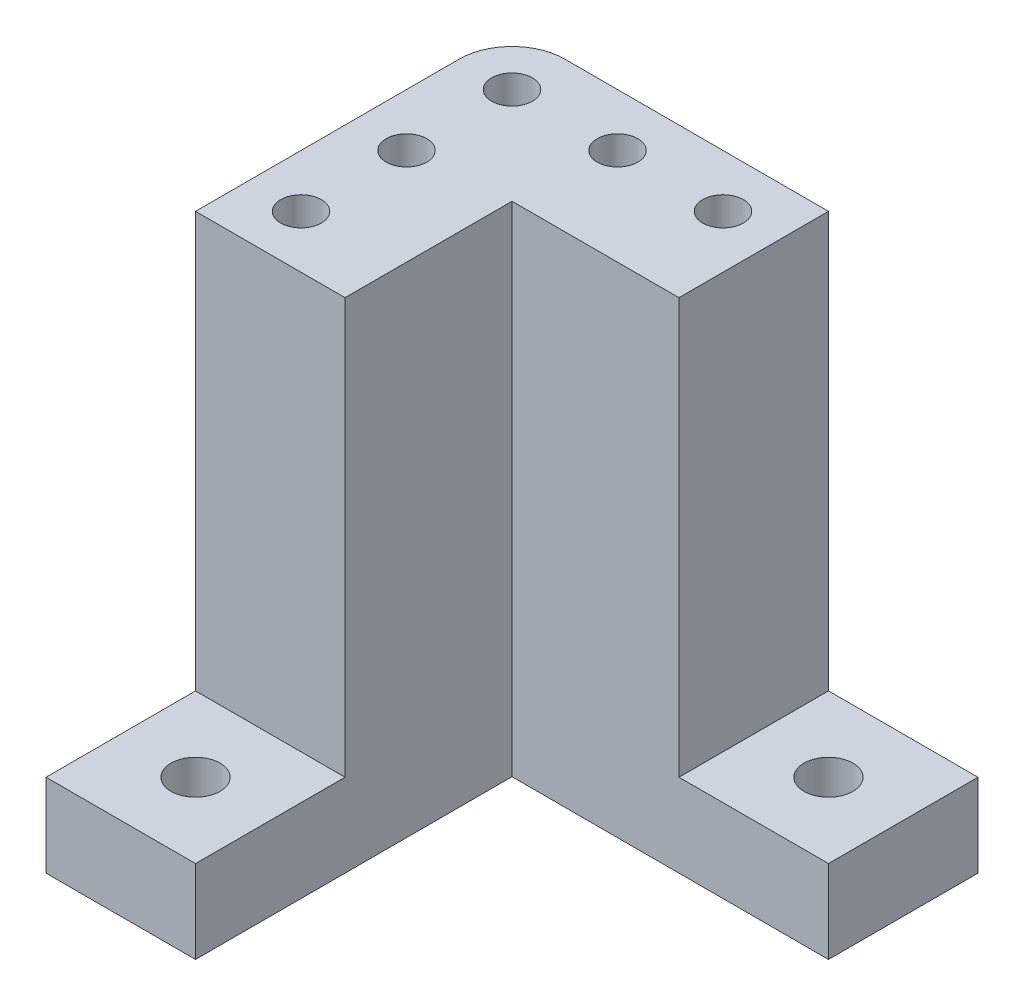
SolidWorks part; units mm, degrees
ref_plane "Front Plane" through (0, 0, 0) normal (0, 0, 1) x (1, 0, 0)
ref_plane "Top Plane" through (0, 0, 0) normal (0, 1, 0) x (1, 0, 0)
ref_plane "Right Plane" through (0, 0, 0) normal (1, 0, 0) x (0, 0, -1)
sketch "Sketch1" plane through (0, 0, 0) normal (0, 1, 0) x (1, 0, 0)
  line L0 (0, 0) -> (38.1, 0)
  line L1 (0, 0) -> (0, -38.1)
  line L2 (0, -38.1) -> (18, -38.1)
  line L3 (18, -38.1) -> (18, -18)
  line L4 (18, -18) -> (38.1, -18)
  line L5 (38.1, -18) -> (38.1, 0)
  dimension "D1" = 38.1
  dimension "D2" = 18
extrude "Boss-Extrude1" add sketch "Sketch1" along normal blind 60
sketch "Sketch2" plane through (0, 60, 0) normal (0, 1, 0) x (1, 0, 0)
  circle A0 centre (6.35, -6.35) radius 2.5527 construction
  circle A1 centre (19.05, -6.35) radius 2.5527 construction
  circle A2 centre (31.75, -6.35) radius 2.5527 construction
  circle A3 centre (6.35, -19.05) radius 2.5527 construction
  circle A4 centre (6.35, -31.75) radius 2.5527 construction
  circle A5 centre (6.35, -6.35) radius 2.45
  circle A6 centre (6.35, -19.05) radius 2.45
  circle A7 centre (6.35, -31.75) radius 2.45
  circle A8 centre (19.05, -6.35) radius 2.45
  circle A9 centre (31.75, -6.35) radius 2.45
  dimension "D1" = 4.9
sketch "Sketch3" plane through (0, 60, 0) normal (0, 1, 0) x (1, 0, 0)
  line L0 (0, -6.35) -> (-3.0233, -6.35)
  line L1 (-3.0233, -6.35) -> (-3.0233, 2.9319)
  line L2 (-3.0233, 2.9319) -> (6.35, 2.9319)
  line L3 (6.35, 2.9319) -> (6.35, 0)
  arc A0 (6.35, 0) -> (0, -6.35) centre (6.35, -6.35) ccw
extrude "Cut-Extrude1" cut sketch "Sketch2" against normal through all
extrude "Cut-Extrude2" cut sketch "Sketch3" against normal through all
sketch "Sketch4" plane through (0, 0, 0) normal (0, -1, 0) x (-1, 0, 0)
  line L0 (0, -38.1) -> (0, -56.1)
  line L1 (-18, -38.1) -> (-18, -56.1)
  line L2 (-18, -56.1) -> (0, -56.1)
  line L3 (0, -38.1) -> (-18, -38.1)
  line L4 (-38.1, -18) -> (-38.1, 0)
  line L5 (-38.1, 0) -> (-56.1, 0)
  line L6 (-56.1, 0) -> (-56.1, -18)
  line L7 (-56.1, -18) -> (-38.1, -18)
  line L8 (0, -56.1) -> (-18, -38.1) construction
  line L9 (-38.1, 0) -> (-56.1, -18) construction
  circle A0 centre (-9, -47.1) radius 2.95
  circle A1 centre (-47.1, -9) radius 2.95
  dimension "D1" = 5.9
extrude "Boss-Extrude2" add sketch "Sketch4" against normal blind 10
